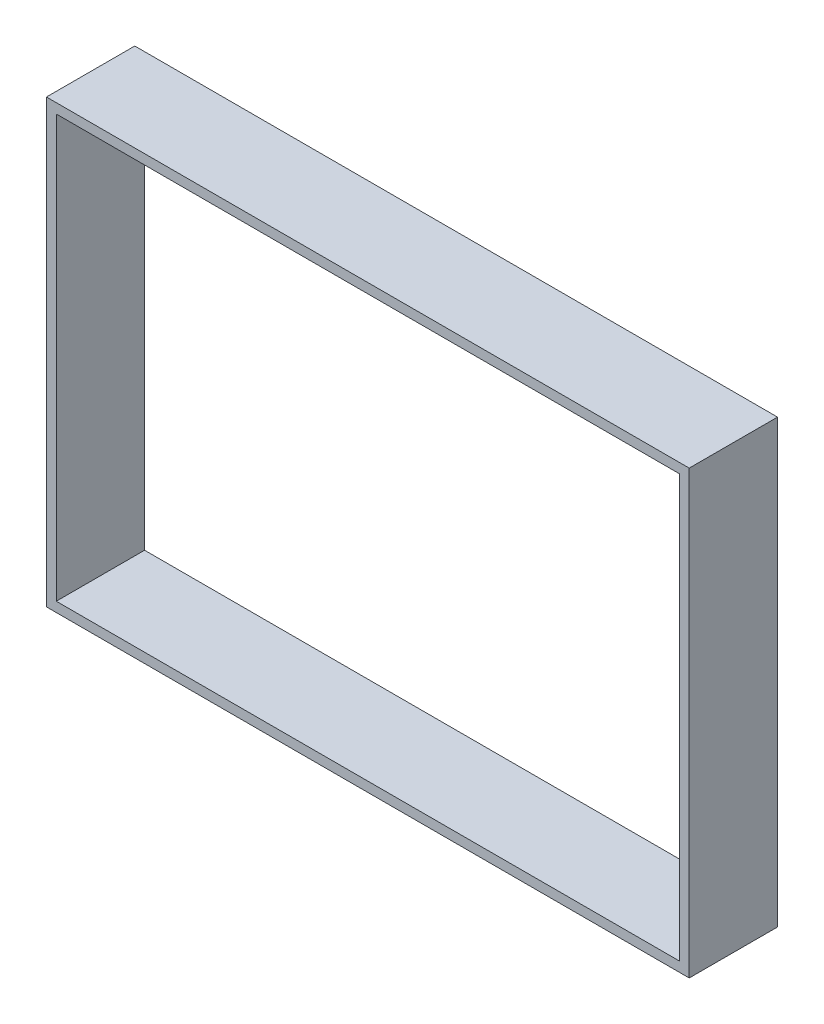
SolidWorks part; units mm, degrees
ref_plane "Front Plane" through (0, 0, 0) normal (0, 0, 1) x (1, 0, 0)
ref_plane "Top Plane" through (0, 0, 0) normal (0, 1, 0) x (1, 0, 0)
ref_plane "Right Plane" through (0, 0, 0) normal (1, 0, 0) x (0, 0, -1)
sketch "Sketch1" plane through (0, 0, 0) normal (0, 0, 1) x (1, 0, 0)
  line L5 (-70.9068, 31.0242) -> (60.0932, 31.0242)
  line L6 (-70.9068, 31.0242) -> (-70.9068, -58.9758)
  line L7 (-70.9068, -58.9758) -> (60.0932, -58.9758)
  line L8 (60.0932, 31.0242) -> (60.0932, -58.9758)
  line L9 (-68.9068, 29.0242) -> (58.0932, 29.0242)
  line L10 (-68.9068, 29.0242) -> (-68.9068, -56.9758)
  line L11 (-68.9068, -56.9758) -> (58.0932, -56.9758)
  line L12 (58.0932, 29.0242) -> (58.0932, -56.9758)
  point P8 (0, 0)
  dimension "D1" = 127
  dimension "D2" = 86
  dimension "D3" = 131
  dimension "D4" = 90
  dimension "D5" = 2
  dimension "D6" = 2
extrude "Boss-Extrude1" add sketch "Sketch1" along normal blind 18
